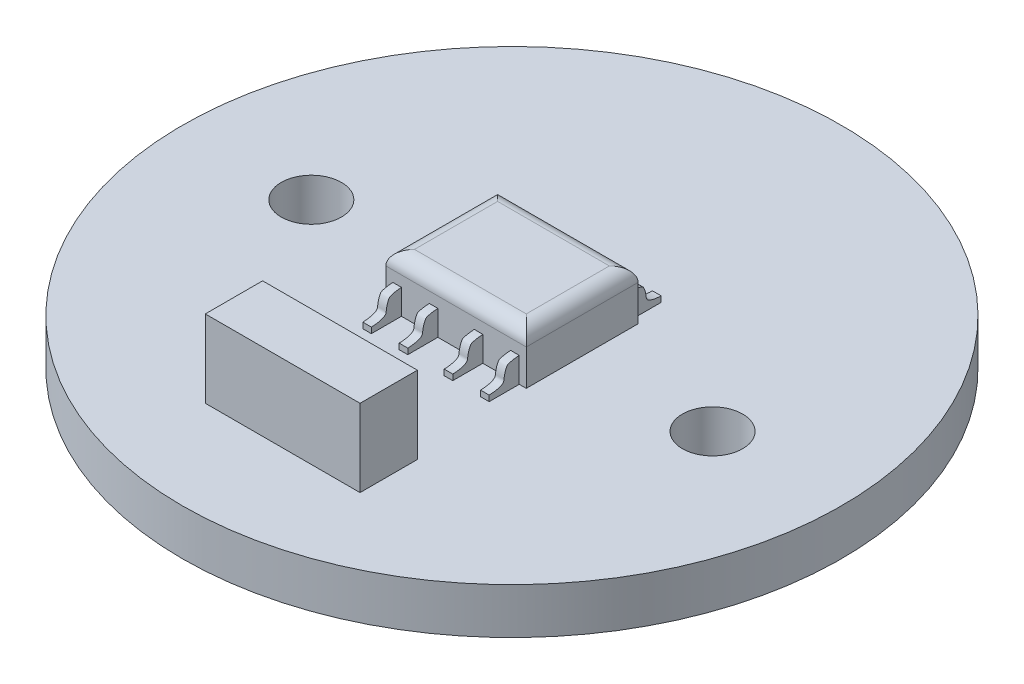
SolidWorks part; units mm, degrees
ref_plane "Front Plane" through (0, 0, 0) normal (0, 0, 1) x (1, 0, 0)
ref_plane "Top Plane" through (0, 0, 0) normal (0, 1, 0) x (1, 0, 0)
ref_plane "Right Plane" through (0, 0, 0) normal (1, 0, 0) x (0, 0, -1)
sketch "Sketch1" plane through (0, 0, 0) normal (0, 1, 0) x (1, 0, 0)
  circle A0 centre (0, 0) radius 11.5
  circle A1 centre (0, 0) radius 7 construction
  circle A2 centre (-7, 0) radius 1.05
  circle A3 centre (7, 0) radius 1.05
  dimension "D1" = 23
  dimension "D2" = 14
  dimension "D3" = 2.1
extrude "Boss-Extrude1" add sketch "Sketch1" along normal blind 1.6
sketch "Sketch2" plane through (0, 1.6, 0) normal (0, 1, 0) x (1, 0, 0)
  line L0 (0, -0.88) -> (0, 0.88) construction
  line L1 (-2.45, 1.95) -> (2.45, 1.95)
  line L2 (-2.45, 1.95) -> (-2.45, -1.95)
  line L3 (-2.45, -1.95) -> (2.45, -1.95)
  line L4 (2.45, 1.95) -> (2.45, -1.95)
  line L5 (-2.45, 1.95) -> (2.45, -1.95) construction
  line L6 (-2.45, -1.95) -> (2.45, 1.95) construction
  point P0 (0, 0)
  dimension "D1" = 4.9
  dimension "D2" = 3.9
extrude "Boss-Extrude2" add sketch "Sketch2" along normal blind 1.75
sketch "Sketch3" plane through (0, 1.6, 0) normal (0, 1, 0) x (1, 0, 0)
  line L0 (-2.45, -1.95) -> (2.45, -1.95) construction
  line L1 (-2.205, -1.95) -> (-1.905, -1.95)
  line L2 (-2.205, -1.95) -> (-2.205, -3)
  line L3 (-2.205, -3) -> (-1.905, -3)
  line L4 (-1.905, -1.95) -> (-1.905, -3)
  line L5 (0, -0.88) -> (0, 0.88) construction
  line L6 (-0.935, -1.95) -> (-0.635, -1.95)
  line L7 (-0.935, -1.95) -> (-0.935, -3)
  line L8 (-0.935, -3) -> (-0.635, -3)
  line L9 (-0.635, -1.95) -> (-0.635, -3)
  point P10 (-2.055, -3)
  point P11 (-0.785, -3)
  dimension "D1" = 1.05
  dimension "D2" = 1.27
  dimension "D3" = 0.3
  dimension "D4" = 0.635
extrude "Boss-Extrude3" add sketch "Sketch3" along normal blind 0.875
mirror "Mirror1" about plane through (0, 0, 0) normal (1, 0, 0) of "Boss-Extrude3"
mirror "Mirror2" about plane through (0, 0, 0) normal (0, 0, 1) of "Mirror1", "Boss-Extrude3"
fillet "Fillet1" radius 0.5 4 edges at (0, 3.35, 1.95) (-2.45, 3.35, 0) (0, 3.35, -1.95) (2.45, 3.35, 0)
sketch "Sketch4" plane through (2.205, 0, 0) normal (1, 0, 0) x (0, 0, -1)
  line L1 (3, 2.475) -> (3, 1.6) construction
  line L5 (1.95, 2.475) -> (3, 2.475)
  line L6 (3, 2.475) -> (3, 1.8)
  spline S0 degree 3 poles (1.95, 2.475) (2.1128, 2.4691) (2.3554, 2.4188) (2.4061, 2.3158) (2.472, 2.178) (2.4908, 1.8708) (2.8009, 1.8006) (3, 1.8) knots 0 0 0 0 0.320657 0.400503 0.754238 0.818609 1 1 1 1
extrude "Cut-Extrude1" cut sketch "Sketch4" against normal through all both and the other way through all
mirror "Mirror3" about plane through (0, 0, 0) normal (0, 0, 1) of "Cut-Extrude1"
sketch "Sketch5" plane through (0, 1.6, 0) normal (0, 1, 0) x (1, 0, 0)
  line L0 (0, -0.88) -> (0, 0.88) construction
  line L1 (2.7, -8) -> (-2.7, -8)
  line L2 (2.7, -8) -> (2.7, -6)
  line L3 (2.7, -6) -> (-2.7, -6)
  line L4 (-2.7, -8) -> (-2.7, -6)
  line L5 (2.7, -8) -> (-2.7, -6) construction
  line L6 (2.7, -6) -> (-2.7, -8) construction
  circle A0 centre (0, 0) radius 11.5 construction
  point P0 (0, -7)
  dimension "D3" = 3.5
  dimension "D1" = 2
  dimension "D2" = 5.4
extrude "Boss-Extrude4" add sketch "Sketch5" along normal blind 2.7
